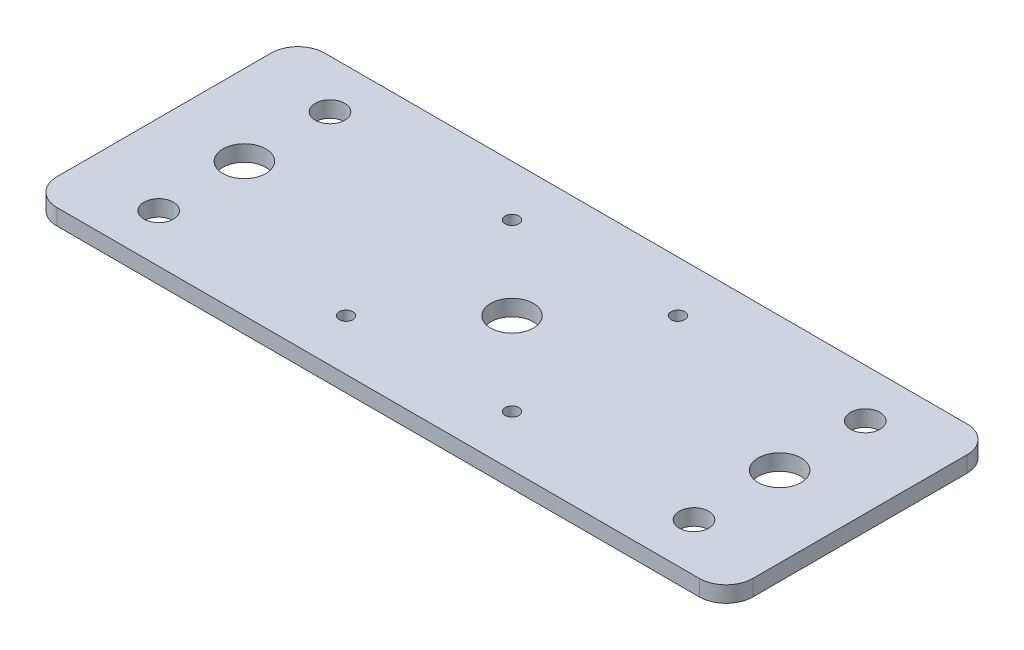
SolidWorks part; units mm, degrees
ref_plane "前视基准面" through (0, 0, 0) normal (0, 0, 1) x (1, 0, 0)
ref_plane "上视基准面" through (0, 0, 0) normal (0, 1, 0) x (1, 0, 0)
ref_plane "右视基准面" through (0, 0, 0) normal (1, 0, 0) x (0, 0, -1)
sketch "草图1" plane through (0, 0, 0) normal (0, 1, 0) x (1, 0, 0)
  line L2 (0, 25) -> (60, 25)
  line L3 (65, 20) -> (65, -20)
  line L4 (60, -25) -> (-60, -25)
  line L5 (-65, -20) -> (-65, 20)
  line L6 (-60, 25) -> (0, 25)
  circle A0 centre (0, 0) radius 4
  circle A2 centre (15.5, 15.5) radius 1.2836
  circle A3 centre (15.5, -15.5) radius 1.2836
  circle A4 centre (-15.5, -15.5) radius 1.2836
  circle A5 centre (-15.5, 15.5) radius 1.2836
  circle A6 centre (50, 0) radius 4
  circle A7 centre (50, 16) radius 2.75
  circle A8 centre (50, -16) radius 2.75
  circle A9 centre (-50, -16) radius 2.75
  circle A10 centre (-50, 16) radius 2.75
  circle A11 centre (-50, 0) radius 4
  arc A12 (-60, -25) -> (-65, -20) centre (-60, -20) cw
  arc A13 (60, -25) -> (65, -20) centre (60, -20) ccw
  arc A14 (65, 20) -> (60, 25) centre (60, 20) ccw
  arc A15 (-65, 20) -> (-60, 25) centre (-60, 20) cw
  point P16 (0, 0)
  dimension "D1" = 4
  dimension "D2" = 50
  dimension "D4" = 5
  dimension "D6" = 8
  dimension "D7" = 8
  dimension "D8" = 8
  dimension "D3" = 32
  dimension "D5" = 50
extrude "凸台-拉伸1" add sketch "草图1" along normal blind 3 contours A15 L5 A12 L4 A13 L3 A14 L2 L6 A10 A0 A2 A3 A4 A5 A6 A7 A8 A9 A11
